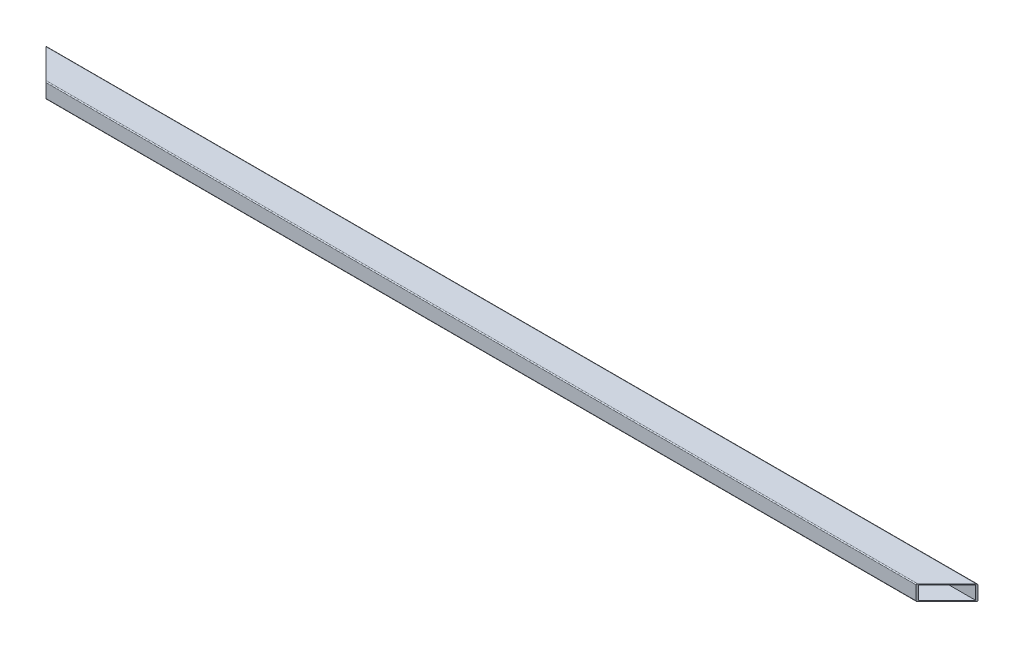
SolidWorks part; units mm, degrees
ref_plane "Front Plane" through (0, 0, 0) normal (0, 0, 1) x (1, 0, 0)
ref_plane "Top Plane" through (0, 0, 0) normal (0, 1, 0) x (1, 0, 0)
ref_plane "Right Plane" through (0, 0, 0) normal (1, 0, 0) x (0, 0, -1)
sketch "Sketch1" plane through (0, 0, 0) normal (1, 0, 0) x (0, 0, -1)
  line L1 (-23.5, 12.5) -> (23.5, 12.5)
  line L2 (-25, 11) -> (-25, -11)
  line L3 (-23.5, -12.5) -> (23.5, -12.5)
  line L4 (25, 11) -> (25, -11)
  line L5 (-25, 12.5) -> (25, -12.5) construction
  line L6 (-25, -12.5) -> (25, 12.5) construction
  arc A0 (-23.5, -12.5) -> (-25, -11) centre (-23.5, -11) cw
  arc A1 (23.5, -12.5) -> (25, -11) centre (23.5, -11) ccw
  arc A2 (25, 11) -> (23.5, 12.5) centre (23.5, 11) ccw
  arc A3 (-25, 11) -> (-23.5, 12.5) centre (-23.5, 11) cw
  point P0 (0, 0)
  dimension "D3" = 1.5
  dimension "D1" = 50
  dimension "D2" = 25
extrude "Boss-Extrude1" add sketch "Sketch1" along normal mid plane 1524
shell "Shell1" thickness 2
sketch "Sketch2" plane through (0, 12.5, 0) normal (0, 1, 0) x (1, 0, 0)
  line L0 (-750, 25) -> (-700, -25)
  line L1 (762, 25) -> (-762, 25) construction
  line L2 (762, -25) -> (-762, -25) construction
  line L4 (0, -13.75) -> (0, 13.75) construction
  line L5 (750, 25) -> (700, -25)
  dimension "D1" = 45
  dimension "D2" = 1500
ref_plane "Plane1" through (-362.5, 0, 362.5) normal (-0.7071, 0, 0.7071) x (0.7071, 0, 0.7071)
other "SurfaceCut1"
ref_plane "Plane2" through (362.5, 0, 362.5) normal (-0.7071, 0, -0.7071) x (-0.7071, 0, 0.7071)
other "SurfaceCut2"
